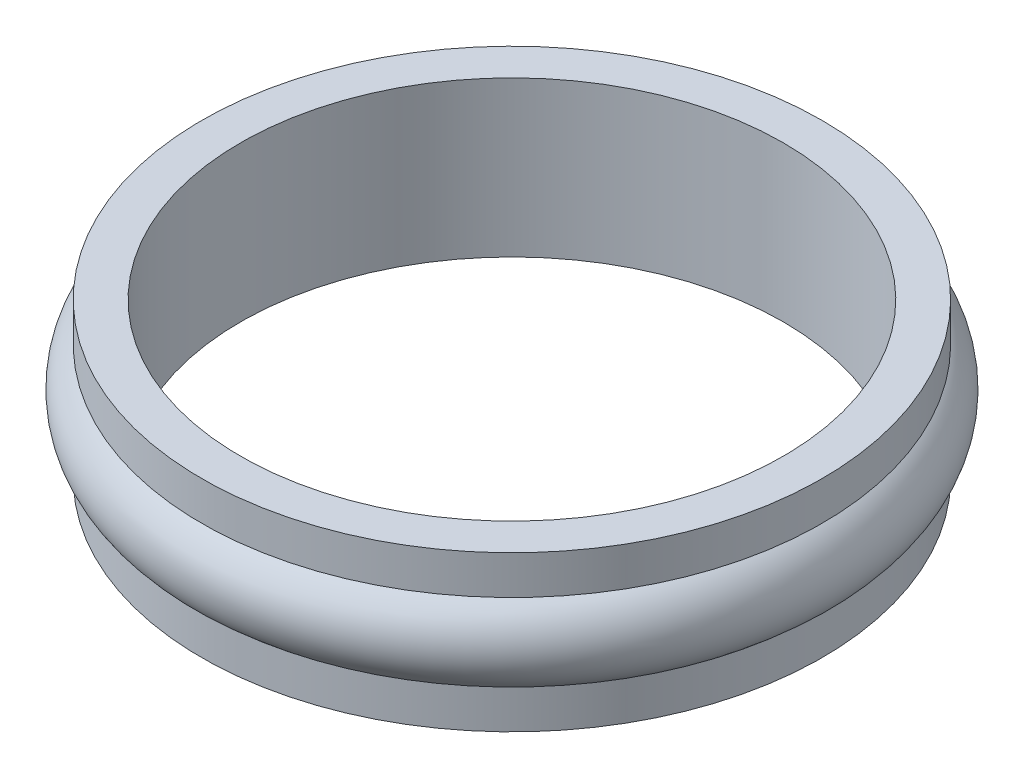
SolidWorks part; units mm, degrees
ref_plane "Front Plane" through (0, 0, 0) normal (0, 0, 1) x (1, 0, 0)
ref_plane "Top Plane" through (0, 0, 0) normal (0, 1, 0) x (1, 0, 0)
ref_plane "Right Plane" through (0, 0, 0) normal (1, 0, 0) x (0, 0, -1)
sketch "Sketch4" plane through (0, 0, 0) normal (0, 0, 1) x (1, 0, 0)
  line L0 (0, 0) -> (0, 31.3146) construction
sketch "Sketch3" plane through (0, 0, 0) normal (0, 0, 1) x (1, 0, 0)
  line L0 (25.4, 0) -> (22.225, 0)
  line L1 (22.225, 12.7) -> (22.225, 0)
  line L2 (22.225, 12.7) -> (25.4, 12.7)
  line L12 (25.4, 12.7) -> (25.4, 9.525)
  line L13 (25.4, 0) -> (25.4, 3.175)
  line L14 (25.4, 9.525) -> (25.4, 3.175) construction
  line L15 (25.4, 6.35) -> (26.9875, 6.35) construction
  arc A0 (25.4, 9.525) -> (25.4, 3.175) centre (23.0187, 6.35) cw
  dimension "D2" = 3.175
  dimension "D1" = 3.175
  dimension "D3" = 12.7
  dimension "D4" = 25.4
  dimension "D6" = 1.5875
revolve "Revolve3" add sketch "Sketch3" angle 360 about L0
ref_plane "Plane1" through (68.58, 0, 0) normal (1, 0, 0) x (0, 0, -1)
